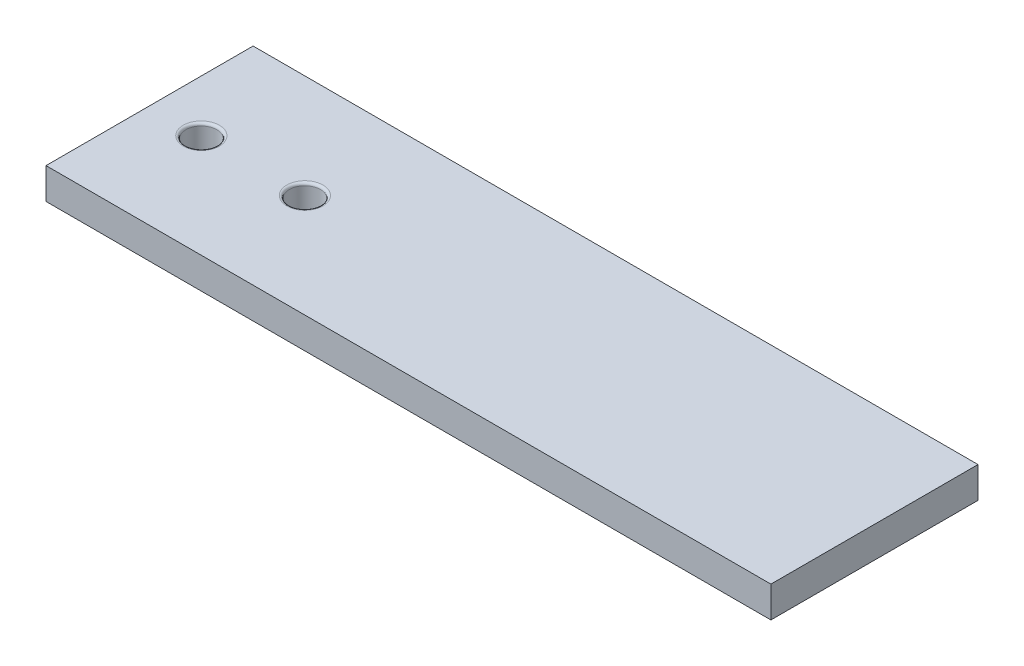
SolidWorks part; units mm, degrees
material "6061-T6 (SS)"
ref_plane "Front Plane" through (0, 0, 0) normal (0, 0, 1) x (1, 0, 0)
ref_plane "Top Plane" through (0, 0, 0) normal (0, 1, 0) x (1, 0, 0)
ref_plane "Right Plane" through (0, 0, 0) normal (1, 0, 0) x (0, 0, -1)
sketch "Sketch1" plane through (0, 0, 0) normal (0, 1, 0) x (1, 0, 0)
  line L1 (70, 20) -> (-70, 20)
  line L2 (70, 20) -> (70, -20)
  line L3 (70, -20) -> (-70, -20)
  line L4 (-70, 20) -> (-70, -20)
  line L5 (70, 20) -> (-70, -20) construction
  line L6 (70, -20) -> (-70, 20) construction
  circle A0 centre (-40, 0) radius 3
  circle A1 centre (-60, 0) radius 3
  point P0 (0, 0)
  dimension "6.2" = 6
  dimension "D2" = 6
  dimension "D3" = 10
  dimension "D4" = 20
  dimension "D5" = 140
  dimension "D6" = 40
extrude "Boss-Extrude1" add sketch "Sketch1" along normal mid plane 6
fillet "Fillet1" radius 0.5 2 edges at (-40, 3, 3) (-60, 3, 3)
